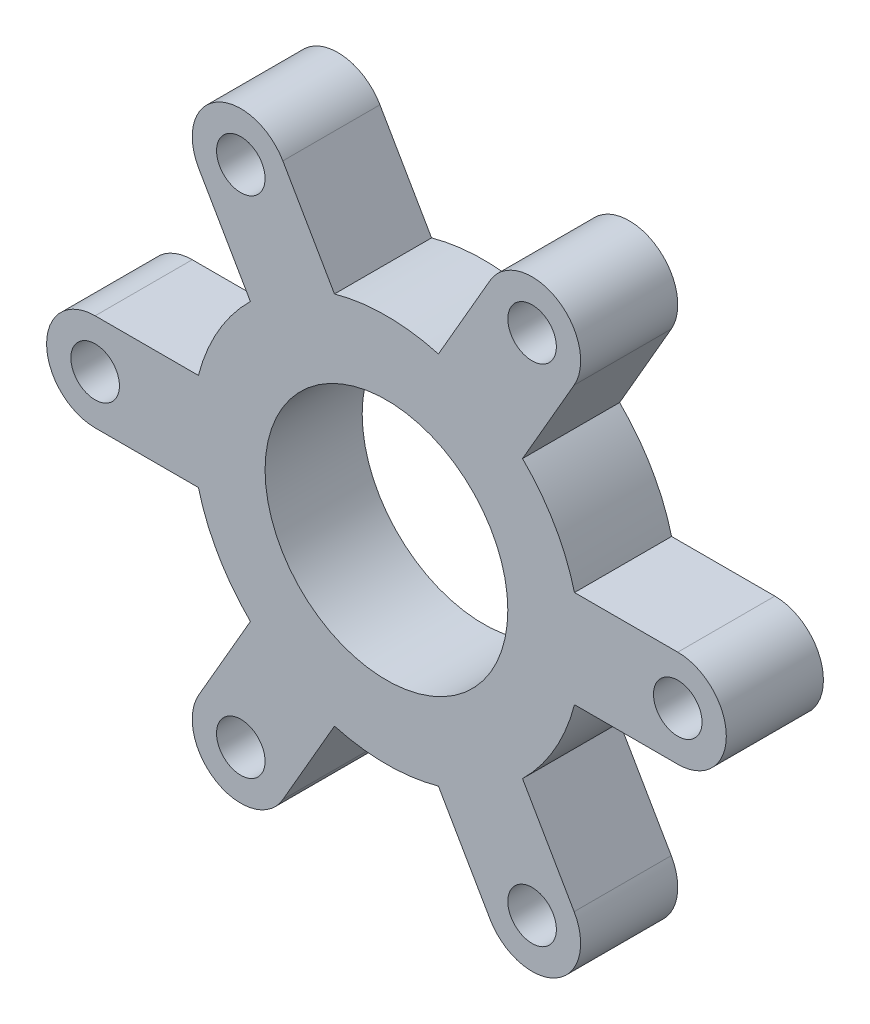
SolidWorks part; units mm, degrees
ref_plane "Front Plane" through (0, 0, 0) normal (0, 0, 1) x (1, 0, 0)
ref_plane "Top Plane" through (0, 0, 0) normal (0, 1, 0) x (1, 0, 0)
ref_plane "Right Plane" through (0, 0, 0) normal (1, 0, 0) x (0, 0, -1)
sketch "Sketch1" plane through (0, 0, 0) normal (0, 0, 1) x (1, 0, 0)
  line L0 (-60, 10) -> (-38.7298, 10)
  line L1 (-60, -10) -> (-38.7298, -10)
  line L2 (-21.3397, 56.9615) -> (-10.7047, 38.541)
  line L3 (-38.6603, 46.9615) -> (-28.0252, 28.541)
  line L4 (38.6603, 46.9615) -> (28.0252, 28.541)
  line L5 (21.3397, 56.9615) -> (10.7047, 38.541)
  line L6 (60, -10) -> (38.7298, -10)
  line L7 (60, 10) -> (38.7298, 10)
  line L8 (21.3397, -56.9615) -> (10.7047, -38.541)
  line L9 (38.6603, -46.9615) -> (28.0252, -28.541)
  line L10 (-38.6603, -46.9615) -> (-28.0252, -28.541)
  line L11 (-21.3397, -56.9615) -> (-10.7047, -38.541)
  circle A0 centre (0, 0) radius 25
  arc A1 (-38.7298, -10) -> (-28.0252, -28.541) centre (0, 0) ccw
  arc A3 (-60, 10) -> (-60, -10) centre (-60, 0) ccw
  circle A4 centre (-60, 0) radius 5
  arc A5 (-21.3397, 56.9615) -> (-38.6603, 46.9615) centre (-30, 51.9615) ccw
  circle A6 centre (-30, 51.9615) radius 5
  arc A7 (38.6603, 46.9615) -> (21.3397, 56.9615) centre (30, 51.9615) ccw
  circle A8 centre (30, 51.9615) radius 5
  arc A9 (60, -10) -> (60, 10) centre (60, 0) ccw
  circle A10 centre (60, 0) radius 5
  arc A11 (21.3397, -56.9615) -> (38.6603, -46.9615) centre (30, -51.9615) ccw
  circle A12 centre (30, -51.9615) radius 5
  arc A13 (-38.6603, -46.9615) -> (-21.3397, -56.9615) centre (-30, -51.9615) ccw
  circle A14 centre (-30, -51.9615) radius 5
  arc A15 (-28.0252, 28.541) -> (-38.7298, 10) centre (0, 0) ccw
  arc A16 (10.7047, 38.541) -> (-10.7047, 38.541) centre (0, 0) ccw
  arc A17 (38.7298, 10) -> (28.0252, 28.541) centre (0, 0) ccw
  arc A18 (28.0252, -28.541) -> (38.7298, -10) centre (0, 0) ccw
  arc A19 (-10.7047, -38.541) -> (10.7047, -38.541) centre (0, 0) ccw
  point P42 (0, 0)
  dimension "D1" = 6
extrude "Boss-Extrude1" add sketch "Sketch1" along normal blind 20
